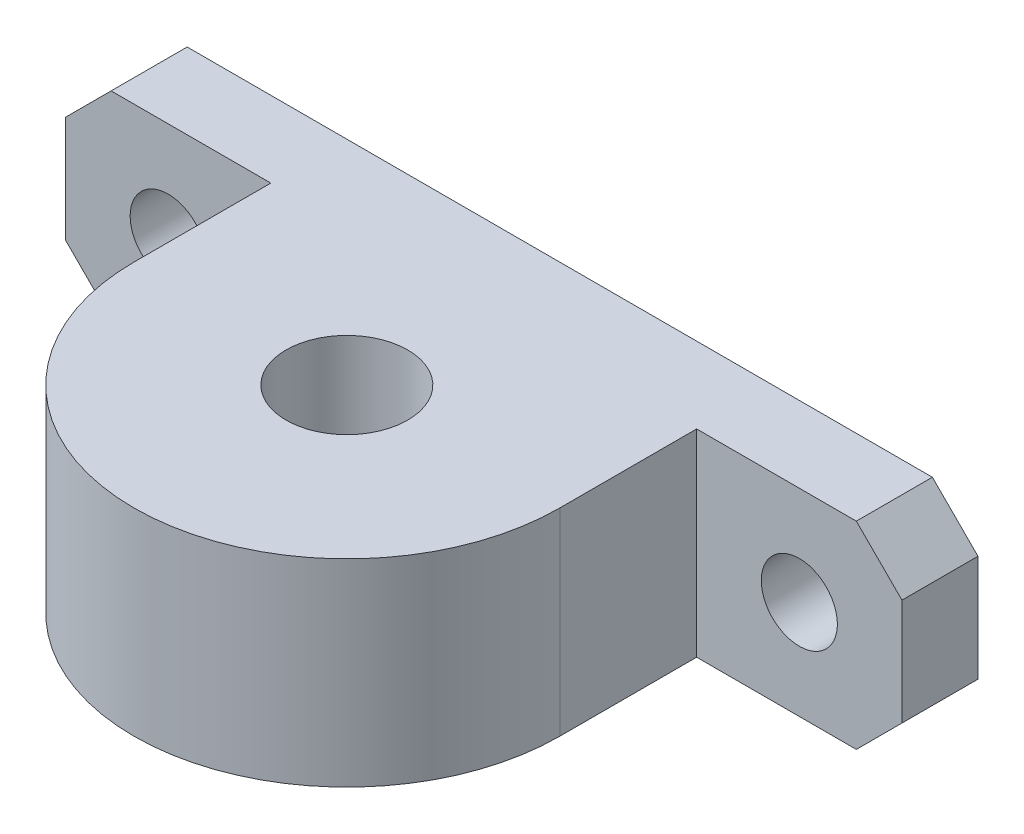
SolidWorks part; units mm, degrees
ref_plane "前视基准面" through (0, 0, 0) normal (0, 0, 1) x (1, 0, 0)
ref_plane "上视基准面" through (0, 0, 0) normal (0, 1, 0) x (1, 0, 0)
ref_plane "右视基准面" through (0, 0, 0) normal (1, 0, 0) x (0, 0, -1)
sketch "草图1" plane through (0, 0, 0) normal (0, 1, 0) x (1, 0, 0)
  line L0 (-14, 0) -> (-14, 9)
  line L1 (14, 14) -> (27.5, 14)
  line L2 (27.5, 14) -> (27.5, 9)
  line L3 (-27.5, 9) -> (-14, 9)
  line L4 (14, 9) -> (14, 0)
  line L5 (-14, 14) -> (-27.5, 14)
  line L6 (-27.5, 14) -> (-27.5, 9)
  line L7 (27.5, 9) -> (14, 9)
  line L8 (-14, 14) -> (14, 14)
  circle A0 centre (0, 0) radius 4
  circle A1 centre (0, 0) radius 14 construction
  arc A2 (0, -14) -> (14, 0) centre (0, 0) ccw
  arc A3 (-14, 0) -> (0, -14) centre (0, 0) ccw
  dimension "D1" = 8
  dimension "D2" = 28
  dimension "D3" = 13.5
  dimension "D4" = 13.5
  dimension "D5" = 5
extrude "凸台-拉伸1" add sketch "草图1" along normal blind 13
sketch "草图2" plane through (0, 0, -14) normal (0, 0, -1) x (-1, 0, 0)
  line L0 (0, 0) -> (0, 6.5) construction
  line L1 (-27.5, 0) -> (27.5, 0) construction
  line L2 (0, 6.5) -> (20.75, 6.5) construction
  line L3 (0, 6.5) -> (-20.75, 6.5) construction
  circle A0 centre (-20.75, 6.5) radius 2.5
  circle A1 centre (20.75, 6.5) radius 2.5
  dimension "D4" = 5
  dimension "D5" = 5
  dimension "D1" = 20.75
  dimension "D2" = 20.75
  dimension "D3" = 6.5
extrude "切除-拉伸1" cut sketch "草图2" against normal up to next
chamfer "倒角1" distance 3 angle 45 4 edges at (27.5, 13, -11.5) (27.5, 0, -11.5) (-27.5, 0, -11.5) (-27.5, 13, -11.5)
